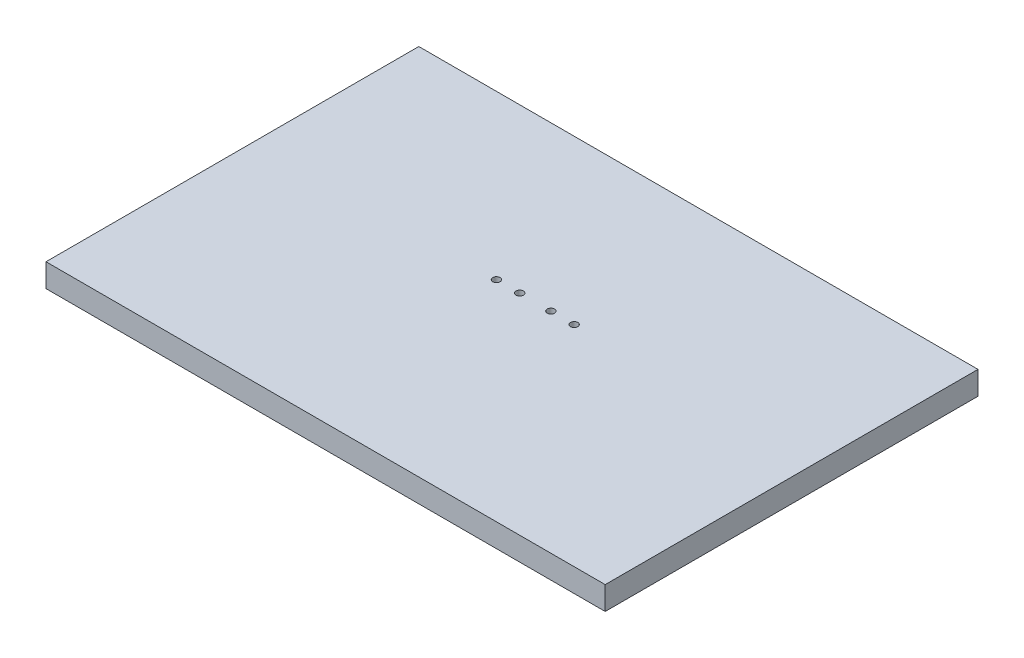
SolidWorks part; units mm, degrees
ref_plane "Front" through (0, 0, 0) normal (0, 0, 1) x (1, 0, 0)
ref_plane "Top" through (0, 0, 0) normal (0, 1, 0) x (1, 0, 0)
ref_plane "Right" through (0, 0, 0) normal (1, 0, 0) x (0, 0, -1)
sketch "Sketch1" plane through (0, 0, 0) normal (0, 1, 0) x (1, 0, 0)
  line L1 (-152.4, -101.6) -> (152.4, -101.6)
  line L2 (-152.4, -101.6) -> (-152.4, 101.6)
  line L3 (-152.4, 101.6) -> (152.4, 101.6)
  line L4 (152.4, -101.6) -> (152.4, 101.6)
  line L5 (-152.4, -101.6) -> (152.4, 101.6) construction
  line L6 (-152.4, 101.6) -> (152.4, -101.6) construction
  point P0 (0, 0)
  dimension "D1" = 203.2
  dimension "D2" = 304.8
extrude "Boss-Extrude1" add sketch "Sketch1" along normal blind 12.7
sketch "Sketch2" plane through (0, 12.7, 0) normal (0, 1, 0) x (1, 0, 0)
  line L0 (152.4, 101.6) -> (-152.4, 101.6) construction
  line L2 (0, 0) -> (0, 26.7306) construction
  circle A0 centre (-21.2, 12.7) radius 2
  circle A1 centre (-8.5, 12.7) radius 2
  circle A2 centre (21.2, 12.7) radius 2
  circle A3 centre (8.5, 12.7) radius 2
  dimension "D3" = 4
  dimension "D1" = 88.9
  dimension "D2" = 17
  dimension "D4" = 12.7
extrude "Cut-Extrude1" cut sketch "Sketch2" against normal through all
